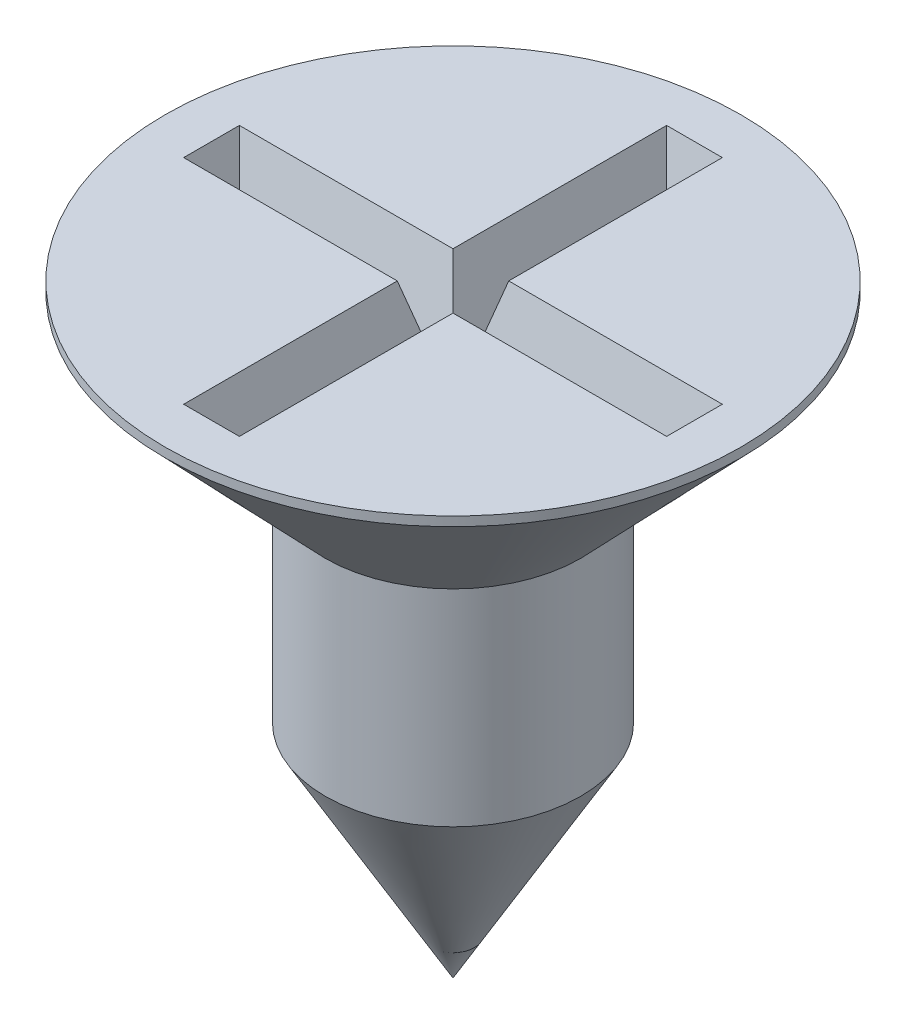
SolidWorks part; units mm, degrees
ref_plane "Front" through (0, 0, 0) normal (0, 0, 1) x (1, 0, 0)
ref_plane "Top" through (0, 0, 0) normal (0, 1, 0) x (1, 0, 0)
ref_plane "Mid" through (0, 0, 0) normal (1, 0, 0) x (0, 0, -1)
sketch "Sketch1" plane through (0, 0, 0) normal (0, 0, 1) x (1, 0, 0)
  line L0 (0, 6.5) -> (0, -6.5) construction
  line L1 (0, 6.5) -> (6.2, 6.5)
  line L2 (6.2, 6.5) -> (6.2, 6.3)
  line L3 (6.2, 6.3) -> (2.75, 2.7)
  line L4 (2.75, 2.7) -> (2.75, -1.7369)
  line L5 (2.75, -1.7369) -> (0, -6.5)
  line L6 (0, -6.5) -> (0, 6.5)
  dimension "C" = 0.2
  dimension "D2" = 30
  dimension "d1" = 12.4
  dimension "k" = 3.8
  dimension "l" = 13
  dimension "d" = 5.5
revolve "Revolve1" add sketch "Sketch1" angle 360 about L0
sketch "Sketch2" plane through (0, 6.5, 0) normal (0, 1, 0) x (-1, 0, 0)
  line L0 (-5.2, 0) -> (5.2, 0) construction
  line L1 (-5.2, -0.6) -> (-0.6, -0.6)
  line L2 (0, 5.2) -> (0, -5.2) construction
  line L3 (-0.6, 5.2) -> (-0.6, 0.6)
  line L4 (-5.2, 0.6) -> (-0.6, 0.6)
  line L5 (0.6, 5.2) -> (0.6, 0.6)
  line L6 (-5.2, -0.6) -> (-5.2, 0.6)
  line L7 (5.2, -0.6) -> (5.2, 0.6)
  line L8 (-0.6, 5.2) -> (0.6, 5.2)
  line L9 (-0.6, -5.2) -> (0.6, -5.2)
  line L10 (-0.6, -0.6) -> (-0.6, -5.2)
  line L11 (-0.6, 5.2) -> (-0.6, -5.2) construction
  line L12 (0.6, -0.6) -> (5.2, -0.6)
  line L13 (-5.2, -0.6) -> (5.2, -0.6) construction
  line L14 (0.6, -0.6) -> (0.6, -5.2)
  line L15 (0.6, 5.2) -> (0.6, -5.2) construction
  line L16 (0.6, 0.6) -> (5.2, 0.6)
  line L17 (-5.2, 0.6) -> (5.2, 0.6) construction
  circle A0 centre (0, 0) radius 6.2 construction
  dimension "D3" = 1
  dimension "D1" = 0.6
  dimension "D2" = 0.6
extrude "Cut-Extrude1" cut sketch "Sketch2" against normal blind 1.9 draft 15
equation "\"D1@Sketch2\" = \"D2@Sketch2\""
equation "\"D1@Cut-Extrude1\" = \"k@Sketch1\" / 2"
